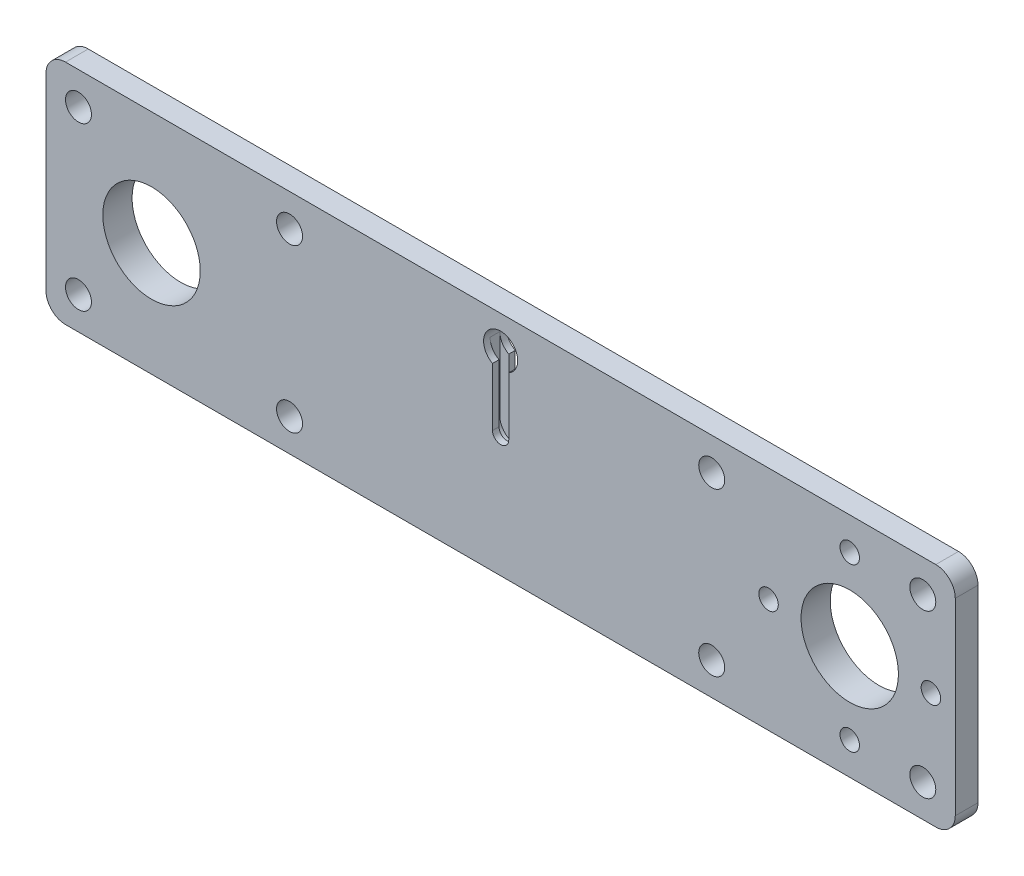
SolidWorks part; units mm, degrees
ref_plane "Ön Düzlem" through (0, 0, 0) normal (0, 0, 1) x (1, 0, 0)
ref_plane "Üst Düzlem" through (0, 0, 0) normal (0, 1, 0) x (1, 0, 0)
ref_plane "Sağ Düzlem" through (0, 0, 0) normal (1, 0, 0) x (0, 0, -1)
sketch "Sketch1" plane through (0, 0, 0) normal (0, 0, 1) x (1, 0, 0)
  line L1 (-140, 35) -> (140, 35)
  line L2 (-140, 35) -> (-140, -35)
  line L3 (-140, -35) -> (140, -35)
  line L4 (140, 35) -> (140, -35)
  line L5 (-140, 35) -> (140, -35) construction
  line L6 (-140, -35) -> (140, 35) construction
  point P0 (0, 0)
  dimension "D1" = 70
  dimension "D2" = 280
extrude "Boss-Extrude1" add sketch "Sketch1" along normal blind 7
fillet "Fillet1" radius 6 4 edges at (140, -35, 3.5) (140, 35, 3.5) (-140, -35, 3.5) (-140, 35, 3.5)
sketch "Sketch2" plane through (0, 0, 0) normal (0, 0, -1) x (-1, 0, 0)
  line L0 (-140, -29) -> (-140, 29) construction
  line L1 (140, 29) -> (140, -29) construction
  line L2 (-134, 35) -> (134, 35) construction
  line L3 (0, 22.5) -> (0, 2.5) construction
  line L4 (107.5, 0) -> (-107.5, 0) construction
  line L5 (130, 25) -> (-130, 25) construction
  line L6 (130, 25) -> (130, -25) construction
  line L7 (130, -25) -> (-130, -25) construction
  line L8 (-130, 25) -> (-130, -25) construction
  line L9 (130, 25) -> (-130, -25) construction
  line L10 (130, -25) -> (-130, 25) construction
  line L11 (2.5, 20.3835) -> (2.5, 2.5)
  line L12 (-2.5, 20.3835) -> (-2.5, 2.5)
  circle A0 centre (-107.5, 0) radius 15
  circle A1 centre (107.5, 0) radius 15
  circle A2 centre (130, 25) radius 4
  circle A3 centre (65, 25) radius 4
  circle A5 centre (-65, 25) radius 4
  circle A6 centre (-130, 25) radius 4
  circle A7 centre (-130, -25) radius 4
  circle A8 centre (-65, -25) radius 4
  arc A9 (2.5, 20.3835) -> (-2.5, 20.3835) centre (0, 25) ccw
  circle A10 centre (65, -25) radius 4
  circle A11 centre (130, -25) radius 4
  circle A12 centre (-132.5, 0) radius 3
  arc A13 (-2.5, 2.5) -> (2.5, 2.5) centre (0, 2.5) ccw
  circle A19 centre (-107.5, 25) radius 3
  circle A20 centre (-107.5, -25) radius 3
  circle A21 centre (-82.5, 0) radius 3
  arc A22 (2.6458, 22) -> (-2.6458, 22) centre (0, 25) ccw [skipped]
  point P9 (140, 0)
  point P10 (0, 0)
  point P22 (0, 12.5)
  point P43 (-2.5, 20.3835)
  point P44 (2.5, 20.3835)
  dimension "D1" = 32.5
  dimension "D2" = 30
  dimension "D3" = 32.5
  dimension "D4" = 30
  dimension "D5" = 10
  dimension "D6" = 10
  dimension "D7" = 8
  dimension "D8" = 5
  dimension "D9" = 25
  dimension "D10" = 10.5
  dimension "D12" = 6
  dimension "D13" = 6
  dimension "D14" = 6
  dimension "D16" = 6
  dimension "D18" = 5
  dimension "D11" = 25
  dimension "D15" = 25
  dimension "D17" = 25
extrude "Cut-Extrude1" cut sketch "Sketch2" against normal blind 10
sketch "Sketch3" plane through (0, 0, 0) normal (0, 0, -1) x (-1, 0, 0)
  circle A0 centre (-107.5, 0) radius 15
  circle A1 centre (-107.5, 0) radius 20
  circle A2 centre (107.5, 0) radius 15
  circle A3 centre (107.5, 0) radius 20
  dimension "D1" = 40
  dimension "D2" = 40
extrude "Boss-Extrude2" add sketch "Sketch3" along normal blind 2
ref_plane "Plane1" through (0, 0, 5) normal (0, 0, 1) x (1, 0, 0)
sketch "Sketch4" plane through (0, 0, 5) normal (0, 0, 1) x (1, 0, 0)
  line L9 (-5.25, 20.3835) -> (-5.25, 25)
  line L11 (5.25, 2.5) -> (5.25, 20.3835)
  line L12 (-5.25, 20.3835) -> (-5.25, 2.5)
  line L13 (5.25, 2.5) -> (5.25, 20.3835)
  line L14 (-5.25, 20.3835) -> (-5.25, 2.5)
  line L15 (5.25, 25) -> (5.25, 20.3835)
  line L16 (0, 25) -> (-5.25, 25)
  line L17 (0, 25) -> (5.25, 25)
  arc A6 (-5.25, 2.5) -> (5.25, 2.5) centre (0, 2.5) ccw
  arc A7 (-5.25, 2.5) -> (5.25, 2.5) centre (0, 2.5) ccw
  dimension "D1" = 2.75
extrude "Cut-Extrude2" cut sketch "Sketch4" against normal blind 3
